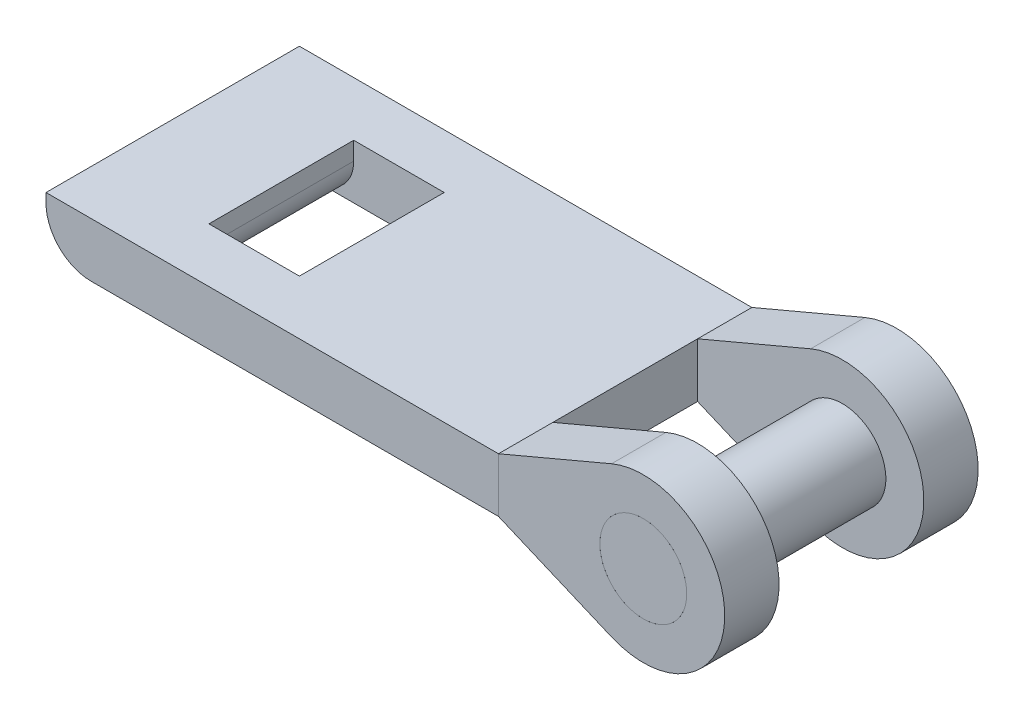
SolidWorks part; units mm, degrees
ref_plane "Спереди" through (0, 0, 0) normal (0, 0, 1) x (1, 0, 0)
ref_plane "Сверху" through (0, 0, 0) normal (0, 1, 0) x (1, 0, 0)
ref_plane "Справа" through (0, 0, 0) normal (1, 0, 0) x (0, 0, -1)
sketch "Эскиз1" plane through (0, 0, 0) normal (0, 0, 1) x (1, 0, 0)
  circle A3 centre (12.9996, 35.1972) radius 2.4
extrude "Бобышка-Вытянуть1" add sketch "Эскиз1" along normal mid plane 14
sketch "Эскиз2" plane through (0, 0, -7) normal (0, 0, -1) x (-1, 0, 0)
  line L0 (-11.2454, 39.3412) -> (-4.9996, 36.6972)
  line L1 (-11.2454, 31.0532) -> (-4.9996, 33.6972)
  line L2 (-4.9996, 33.6972) -> (-4.9996, 36.6972)
  line L3 (-12.9996, 35.1972) -> (-11.8152, 35.1972) construction
  circle A3 centre (-12.9996, 35.1972) radius 2.4
  arc A4 (-11.2454, 39.3412) -> (-11.2454, 31.0532) centre (-12.9996, 35.1972) ccw
  dimension "D3" = 4.5
  dimension "D4" = 3
extrude "Бобышка-Вытянуть2" add sketch "Эскиз2" against normal blind 3 separate body
mirror "Зеркальное отражение2" about plane through (0, 0, 0) normal (0, 0, 1) of bodies 102
sketch "Эскиз3" plane through (4.9996, 0, 0) normal (-1, 0, 0) x (0, 0, 1)
  line L4 (-7, 36.6972) -> (-7, 33.6972)
  line L5 (-7, 33.6972) -> (-4, 33.6972)
  line L6 (-4, 33.6972) -> (-4, 36.6972)
  line L7 (-4, 36.6972) -> (-7, 36.6972)
  line L8 (-7, 36.6972) -> (-7, 33.6972)
  line L9 (-7, 33.6972) -> (7, 33.6972)
  line L11 (7, 36.6972) -> (-7, 36.6972)
  line L12 (7, 33.6972) -> (7, 36.6972)
  line L13 (7, 36.6972) -> (4, 36.6972)
  line L14 (4, 36.6972) -> (4, 33.6972)
  line L15 (4, 33.6972) -> (7, 33.6972)
  line L16 (7, 33.6972) -> (7, 36.6972)
  dimension "D1" = 0
  dimension "D2" = 0
extrude "Бобышка-Вытянуть3" add sketch "Эскиз3" along normal blind 22 separate body
sketch "Эскиз4" plane through (0, 36.6972, 0) normal (0, 1, 0) x (1, 0, 0)
  line L0 (-19.1941, 0) -> (8.0202, 0) construction
  line L1 (-17.0004, -7) -> (-17.0004, 7) construction
  line L2 (-9.0004, -4) -> (-14.0004, -4)
  line L3 (-9.0004, -4) -> (-9.0004, 4)
  line L4 (-9.0004, 4) -> (-14.0004, 4)
  line L5 (-14.0004, -4) -> (-14.0004, 4)
  line L6 (-9.0004, -4) -> (-14.0004, 4) construction
  line L7 (-9.0004, 4) -> (-14.0004, -4) construction
  line L8 (-17.0004, 7) -> (4.9996, 7) construction
  point P3 (-11.5004, 0)
  dimension "D1" = 3
  dimension "D2" = 3
  dimension "D3" = 5
extrude "Вырез-Вытянуть4" cut sketch "Эскиз4" against normal through all
fillet "Скругление1" radius 2 1 edges at (-14.0004, 33.6972, 0)
sketch "Эскиз5" plane through (-17.0004, 0, 0) normal (-1, 0, 0) x (0, 0, 1)
  line L6 (7, 36.6972) -> (-7, 36.6972)
  line L7 (-7, 36.6972) -> (-7, 33.6972)
  line L8 (-7, 33.6972) -> (7, 33.6972)
  line L11 (7, 33.6972) -> (7, 36.6972)
  line L12 (7, 36.6972) -> (-7, 36.6972)
  line L13 (-7, 36.6972) -> (-7, 33.6972)
  line L14 (-7, 33.6972) -> (7, 33.6972)
  line L17 (7, 33.6972) -> (7, 36.6972)
  dimension "D1" = 0
extrude "Бобышка-Вытянуть4" add sketch "Эскиз5" along normal blind 3
fillet "Скругление2" radius 2.5 1 edges at (-20.0004, 33.6972, 0)
